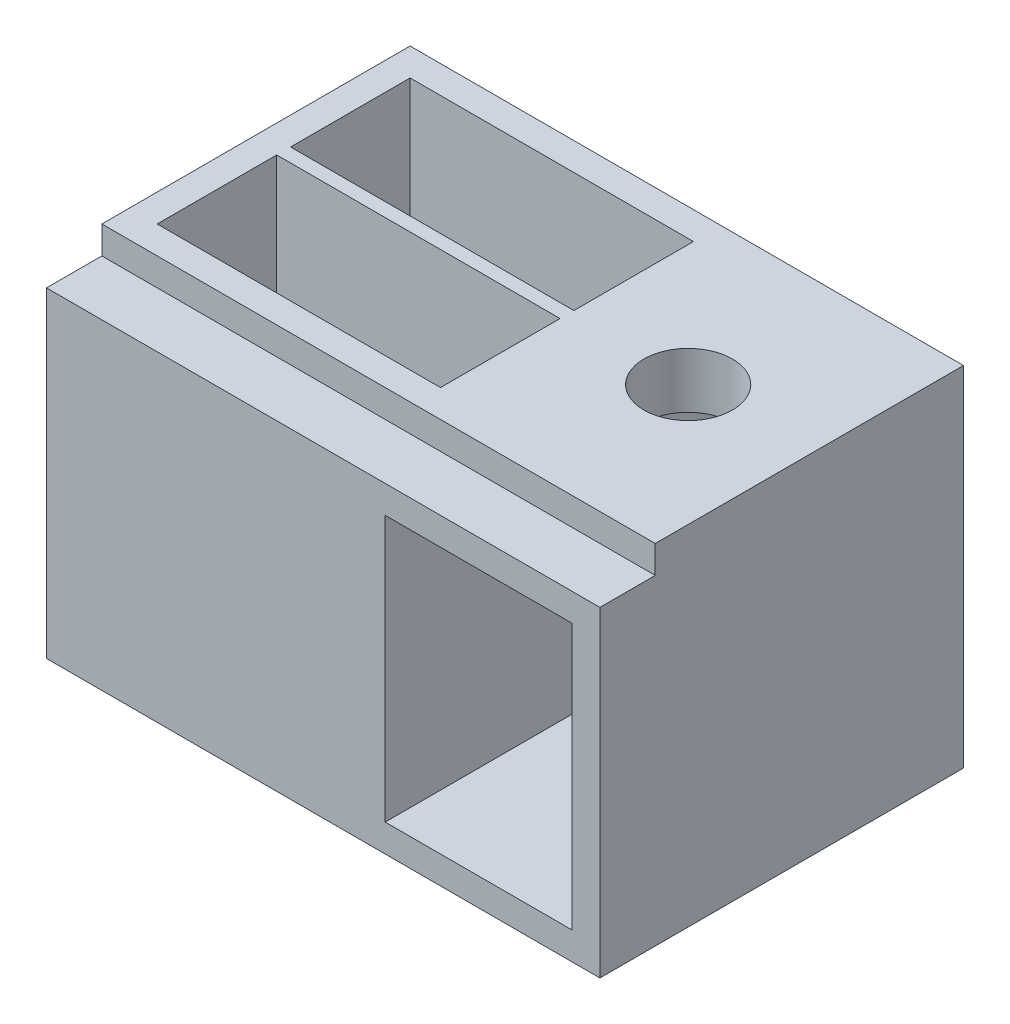
SolidWorks part; units mm, degrees
material "ABS"
ref_plane "Front Plane" through (0, 0, 0) normal (0, 0, 1) x (1, 0, 0)
ref_plane "Top Plane" through (0, 0, 0) normal (0, 1, 0) x (1, 0, 0)
ref_plane "Right Plane" through (0, 0, 0) normal (1, 0, 0) x (0, 0, -1)
sketch "Sketch1" plane through (0, 0, 0) normal (0, 1, 0) x (1, 0, 0)
  line L0 (3.175, 18.4785) -> (3.175, 32.1945)
  line L1 (0, 0) -> (63.5, 0)
  line L2 (0, 0) -> (0, 44.45)
  line L3 (0, 44.45) -> (63.5, 44.45)
  line L4 (63.5, 0) -> (63.5, 44.45)
  line L5 (4.445, 4.445) -> (34.417, 4.445)
  line L6 (4.445, 4.445) -> (4.445, 15.621)
  line L7 (4.445, 15.621) -> (34.417, 15.621)
  line L8 (34.417, 4.445) -> (34.417, 15.621)
  line L9 (4.445, 19.7485) -> (34.417, 19.7485)
  line L10 (4.445, 19.7485) -> (4.445, 30.9245)
  line L11 (4.445, 30.9245) -> (34.417, 30.9245)
  line L12 (34.417, 19.7485) -> (34.417, 30.9245)
  line L13 (3.175, 32.1945) -> (35.687, 32.1945)
  line L14 (35.687, 18.4785) -> (35.687, 32.1945)
  line L15 (3.175, 18.4785) -> (35.687, 18.4785)
  line L16 (3.175, 3.175) -> (35.687, 3.175)
  line L17 (35.687, 3.175) -> (35.687, 16.891)
  line L18 (3.175, 16.891) -> (35.687, 16.891)
  line L19 (3.175, 3.175) -> (3.175, 16.891)
  dimension "D1" = 44.45
  dimension "D2" = 63.5
  dimension "D3" = 11.176
  dimension "D4" = 29.972
  dimension "D5" = 11.176
  dimension "D6" = 29.972
  dimension "D9" = 1.5875
  dimension "D10" = 3.175
  dimension "D11" = 3.175
  dimension "D7" = 1.27
  dimension "D8" = 1.27
extrude "Boss-Extrude1" add sketch "Sketch1" along normal blind 40.005
sketch "Sketch2" plane through (0, 0, 0) normal (0, -1, 0) x (1, 0, 0)
  line L0 (3.175, -32.1945) -> (35.687, -32.1945) construction
  line L1 (3.175, -18.4785) -> (3.175, -32.1945) construction
  line L2 (3.175, -18.4785) -> (35.687, -18.4785) construction
  line L3 (35.687, -18.4785) -> (35.687, -32.1945) construction
  line L4 (0, 0) -> (0, -44.45)
  line L5 (0, -44.45) -> (63.5, -44.45)
  line L6 (63.5, -44.45) -> (63.5, 0)
  line L7 (63.5, 0) -> (0, 0)
  line L8 (0, 0) -> (0, -44.45)
  line L9 (0, -44.45) -> (63.5, -44.45)
  line L10 (63.5, -44.45) -> (63.5, 0)
  line L11 (63.5, 0) -> (0, 0)
  line L12 (35.687, -3.175) -> (35.687, -16.891) construction
  line L13 (3.175, -3.175) -> (35.687, -3.175) construction
  line L14 (3.175, -3.175) -> (3.175, -16.891) construction
  line L15 (3.175, -16.891) -> (35.687, -16.891) construction
  line L16 (3.175, -32.1945) -> (35.687, -32.1945)
  line L17 (3.175, -18.4785) -> (3.175, -32.1945)
  line L18 (3.175, -18.4785) -> (35.687, -18.4785)
  line L19 (35.687, -18.4785) -> (35.687, -32.1945)
  line L20 (35.687, -3.175) -> (35.687, -16.891)
  line L21 (3.175, -3.175) -> (35.687, -3.175)
  line L22 (3.175, -3.175) -> (3.175, -16.891)
  line L23 (3.175, -16.891) -> (35.687, -16.891)
  line M9 (3.175, -18.4785) -> (35.687, -18.4785)
  line M10 (35.687, -18.4785) -> (35.687, -32.1945)
  line M11 (35.687, -32.1945) -> (3.175, -32.1945)
  line M12 (3.175, -32.1945) -> (3.175, -18.4785)
  line M13 (3.175, -3.175) -> (35.687, -3.175)
  line M14 (35.687, -3.175) -> (35.687, -16.891)
  line M15 (35.687, -16.891) -> (3.175, -16.891)
  line M16 (3.175, -16.891) -> (3.175, -3.175)
  dimension "D1" = 0
extrude "Boss-Extrude2" add sketch "Sketch2" against normal blind 2.54 contours M13 M16 M15 M14 | M9 M12 M11 M10
sketch "Sketch3" plane through (0, 40.005, 0) normal (0, 1, 0) x (1, 0, 0)
  line L33 (35.687, 35.3695) -> (3.175, 35.3695)
  line L34 (35.687, 35.3695) -> (3.175, 35.3695)
  line L36 (0, 32.1945) -> (0, 18.4785)
  line L37 (0, 32.1945) -> (0, 18.4785)
  line L38 (0, 0) -> (63.5, 0) construction
  line L39 (38.862, 18.4785) -> (38.862, 32.1945)
  line L40 (38.862, 18.4785) -> (38.862, 32.1945)
  line L41 (0, 35.3695) -> (38.862, 35.3695)
  line L42 (0, 35.3695) -> (0, 0)
  line L43 (0, 0) -> (38.862, 0)
  line L44 (38.862, 35.3695) -> (38.862, 0)
  line L49 (0, 44.45) -> (0, 0)
  line L50 (0, 0) -> (63.5, 0)
  line L51 (63.5, 0) -> (63.5, 44.45)
  line L52 (63.5, 44.45) -> (0, 44.45)
  line L53 (0, 44.45) -> (0, 0)
  line L54 (0, 0) -> (63.5, 0)
  line L55 (63.5, 0) -> (63.5, 44.45)
  line L56 (63.5, 44.45) -> (0, 44.45)
  line M11 (0, 44.45) -> (0, 0)
  line M12 (0, 0) -> (63.5, 0)
  line M13 (63.5, 0) -> (63.5, 44.45)
  line M14 (63.5, 44.45) -> (0, 44.45)
  dimension "D4" = 0
  dimension "D1" = 3.175
  dimension "D2" = 3.175
  dimension "D3" = 3.175
extrude "Cut-Extrude1" cut sketch "Sketch3" against normal blind 36.83 contours L41 L44 L40 L42 L37 L34 M12 M13 M14 M11
sketch "Sketch9" plane through (0, 0, 0) normal (0, 0, 1) x (1, 0, 0)
  line L0 (38.862, 3.175) -> (38.862, 40.005) construction
  line L1 (0, 40.005) -> (38.862, 40.005)
  line L2 (0, 40.005) -> (0, 36.83)
  line L3 (0, 36.83) -> (38.862, 36.83)
  line L4 (38.862, 40.005) -> (38.862, 36.83)
  line L11 (63.5, 3.175) -> (38.862, 3.175)
  line L12 (38.862, 3.175) -> (38.862, 40.005)
  line L13 (38.862, 40.005) -> (0, 40.005)
  line L14 (0, 40.005) -> (0, 0)
  line L15 (0, 0) -> (63.5, 0)
  line L16 (63.5, 0) -> (63.5, 3.175)
  line L18 (38.862, 3.175) -> (38.862, 40.005)
  line L19 (38.862, 40.005) -> (0, 40.005)
  line L20 (0, 40.005) -> (0, 0)
  line L21 (0, 0) -> (63.5, 0)
  line L22 (63.5, 0) -> (63.5, 3.175)
  line L23 (63.5, 3.175) -> (38.862, 3.175)
  dimension "D1" = 3.175
  dimension "D2" = 0
extrude "Boss-Extrude8" add sketch "Sketch9" along normal blind 6.35
sketch "Sketch10" plane through (0, 0, 6.35) normal (0, 0, 1) x (1, 0, 0)
  line L0 (0, 36.83) -> (38.862, 36.83) construction
  line L1 (63.5, 3.175) -> (60.325, 3.175)
  line L2 (63.5, 3.175) -> (63.5, 36.83)
  line L3 (63.5, 36.83) -> (60.325, 36.83)
  line L4 (60.325, 3.175) -> (60.325, 36.83)
  line L5 (38.862, 3.175) -> (38.862, 36.83) construction
  line L7 (60.325, 36.83) -> (60.325, 33.655)
  line L11 (60.325, 33.655) -> (60.325, 30.48)
  line L14 (60.325, 36.83) -> (38.862, 36.83)
  line L15 (60.325, 36.83) -> (60.325, 33.655)
  line L16 (60.325, 33.655) -> (38.862, 33.655)
  line L17 (38.862, 36.83) -> (38.862, 33.655)
  line M8 (63.5, 3.175) -> (38.862, 3.175)
  line M9 (38.862, 3.175) -> (38.862, 36.83)
  dimension "D1" = 3.175
  dimension "D2" = 3.175
  dimension "D3" = 3.175
extrude "Boss-Extrude9" add sketch "Sketch10" against normal up to surface (50.8 mm away) contours L4 L2 L3 M8 | L16 L4 L14 M9 | L11 up to face at (31.75, 1.5875, -44.45)
sketch "Sketch11" plane through (0, 0, 0) normal (-1, 0, 0) x (0, 0, 1)
  line L1 (-35.3695, 36.83) -> (-44.45, 36.83)
  line L2 (-35.3695, 36.83) -> (-35.3695, 0)
  line L3 (-35.3695, 0) -> (-44.45, 0)
  line L4 (-44.45, 36.83) -> (-44.45, 0)
extrude "Cut-Extrude2" cut sketch "Sketch11" against normal through all
sketch "Sketch12" plane through (0, 0, -35.3695) normal (0, 0, -1) x (-1, 0, 0)
  line L1 (-60.325, 33.655) -> (-38.862, 33.655)
  line L2 (-60.325, 33.655) -> (-60.325, 3.175)
  line L3 (-60.325, 3.175) -> (-38.862, 3.175)
  line L4 (-38.862, 33.655) -> (-38.862, 3.175)
  circle A0 centre (-49.5935, 18.415) radius 5.08
  line M1 (-38.862, 33.655) -> (-38.862, 3.175)
  line M2 (-38.862, 3.175) -> (-60.325, 3.175)
  line M3 (-60.325, 3.175) -> (-60.325, 33.655)
  line M4 (-60.325, 33.655) -> (-38.862, 33.655)
  dimension "D1" = 10.16
extrude "Boss-Extrude10" add sketch "Sketch12" against normal blind 2.54 contours A0 M1 M4 M3 M2
sketch "Sketch13" plane through (0, 36.83, 0) normal (0, 1, 0) x (1, 0, 0)
  line L0 (63.5, 35.3695) -> (63.5, -6.35) construction
  line L1 (38.862, 35.3695) -> (63.5, 35.3695)
  line L2 (38.862, 35.3695) -> (38.862, 0)
  line L3 (38.862, 0) -> (63.5, 0)
  line L4 (63.5, 35.3695) -> (63.5, 0)
extrude "Boss-Extrude11" add sketch "Sketch13" along normal blind 3.175
sketch "Sketch14" plane through (0, 40.005, 0) normal (0, 1, 0) x (1, 0, 0)
  line L0 (0, 0) -> (63.5, 0) construction
  line L1 (35.687, 0) -> (63.5, 0)
  line L2 (35.687, 0) -> (35.687, 35.3695)
  line L3 (35.687, 35.3695) -> (63.5, 35.3695)
  line L4 (63.5, 0) -> (63.5, 35.3695)
  line L5 (63.5, 0) -> (63.5, 35.3695) construction
  line L6 (0, 35.3695) -> (63.5, 35.3695) construction
  circle A0 centre (49.5935, 17.6847) radius 5.08
  dimension "D1" = 10.16
extrude "Cut-Extrude3" cut sketch "Sketch14" against normal up to surface (6.35 mm away) contours A0 up to face at (49.5935, 33.655, -13.2397)
